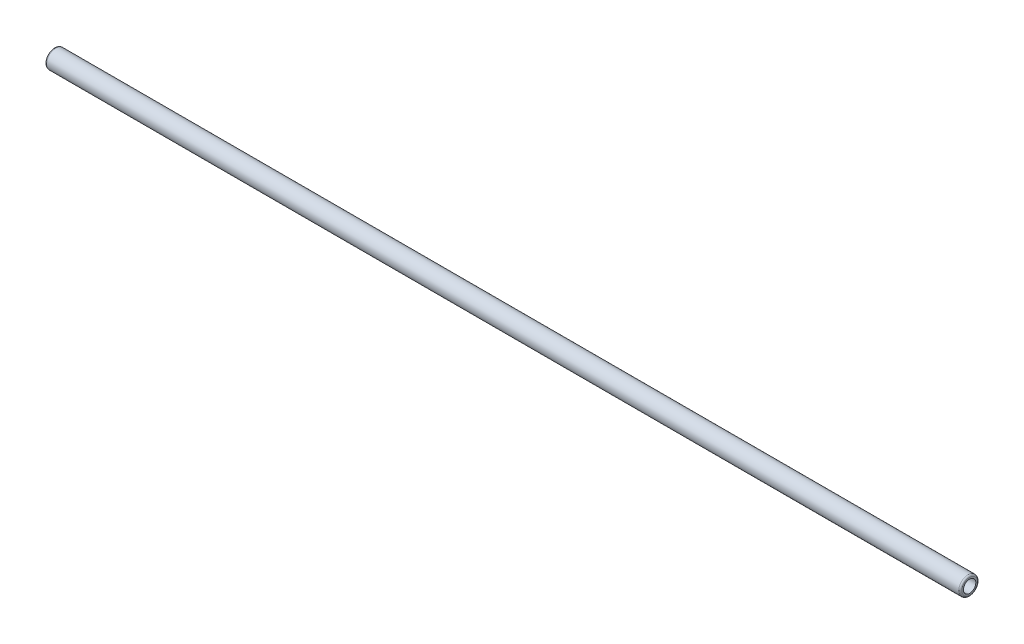
SolidWorks part; units mm, degrees
ref_plane "Спереди" through (0, 0, 0) normal (0, 0, 1) x (1, 0, 0)
ref_plane "Сверху" through (0, 0, 0) normal (0, 1, 0) x (1, 0, 0)
ref_plane "Справа" through (0, 0, 0) normal (1, 0, 0) x (0, 0, -1)
other "Configuration Table"
sketch "Эскиз1" plane through (0, 0, 0) normal (1, 0, 0) x (0, 0, -1)
  circle A0 centre (0, 0) radius 2
  circle A1 centre (0, 0) radius 3
  dimension "D1" = 6
  dimension "D2" = 4
extrude "Бобышка-Вытянуть1" add sketch "Эскиз1" along normal mid plane 296
fillet "Скругление1" radius 0.5 2 edges at (-148, 0, -3) (148, 0, -3)
